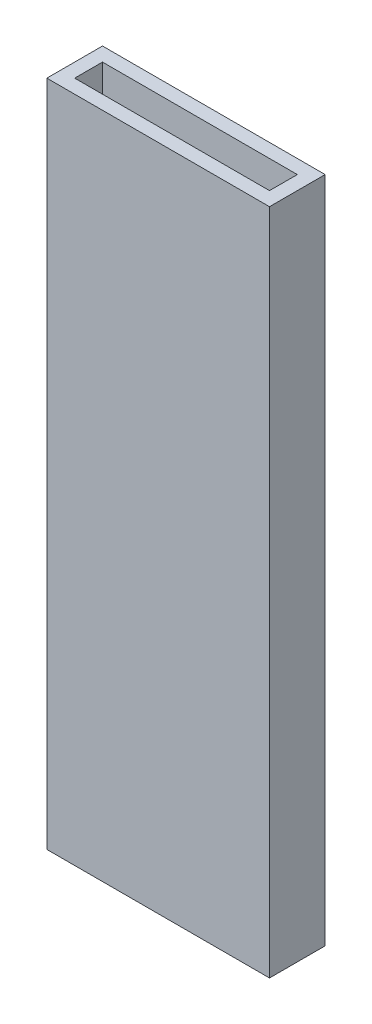
SolidWorks part; units mm, degrees
ref_plane "Front Plane" through (0, 0, 0) normal (0, 0, 1) x (1, 0, 0)
ref_plane "Top Plane" through (0, 0, 0) normal (0, 1, 0) x (1, 0, 0)
ref_plane "Right Plane" through (0, 0, 0) normal (1, 0, 0) x (0, 0, -1)
sketch "Sketch1" plane through (0, 0, 0) normal (0, 1, 0) x (1, 0, 0)
  line L1 (0, 0) -> (25.4, 0)
  line L2 (0, 0) -> (0, 6.35)
  line L3 (0, 6.35) -> (25.4, 6.35)
  line L4 (25.4, 0) -> (25.4, 6.35)
  dimension "D1" = 25.4
  dimension "D2" = 6.35
extrude "Boss-Extrude1" add sketch "Sketch1" along normal blind 76.2
shell "Shell1" thickness 1.5875
